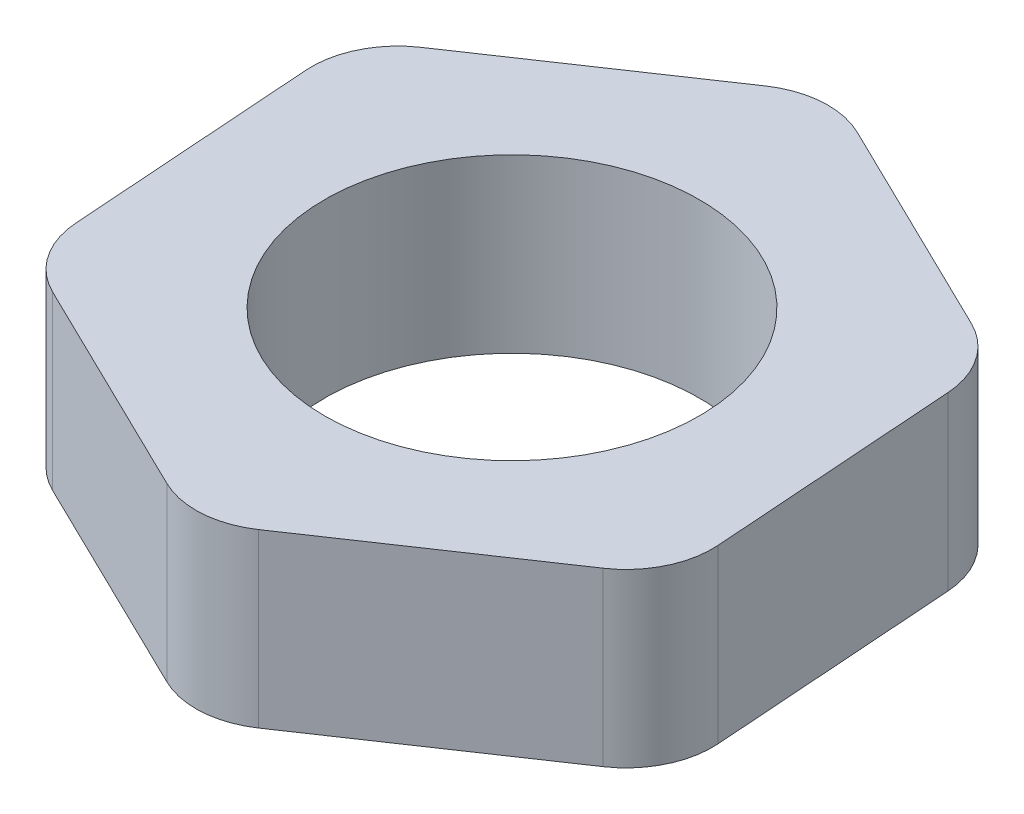
SolidWorks part; units mm, degrees
material "Plain Carbon Steel"
ref_plane "Front" through (0, 0, 0) normal (0, 0, 1) x (1, 0, 0)
ref_plane "Top" through (0, 0, 0) normal (0, 1, 0) x (1, 0, 0)
ref_plane "Right" through (0, 0, 0) normal (1, 0, 0) x (0, 0, -1)
sketch "Sketch1" plane through (0, 0, 0) normal (0, 1, 0) x (1, 0, 0)
  line L1 (-0.1414, 2.0158) -> (-1.8164, 0.8854)
  line L2 (-1.8164, 0.8854) -> (-1.675, -1.1304)
  line L3 (-1.675, -1.1304) -> (0.1414, -2.0158)
  line L4 (0.1414, -2.0158) -> (1.8164, -0.8854)
  line L5 (1.8164, -0.8854) -> (1.675, 1.1304)
  line L6 (1.675, 1.1304) -> (-0.1414, 2.0158)
  circle A0 centre (0, 0) radius 1.09
  circle A1 centre (0, 0) radius 1.75 construction
  dimension "D1" = 2.18
  dimension "D2" = 3.5
  dimension "D3" = 1.675
extrude "Boss-Extrude1" add sketch "Sketch1" along normal blind 1
fillet "Fillet1" radius 0.5 6 edges at (-0.1414, 0.5, -2.0158) (-1.8164, 0.5, -0.8854) (-1.675, 0.5, 1.1304) (0.1414, 0.5, 2.0158) (1.8164, 0.5, 0.8854) (1.675, 0.5, -1.1304)
